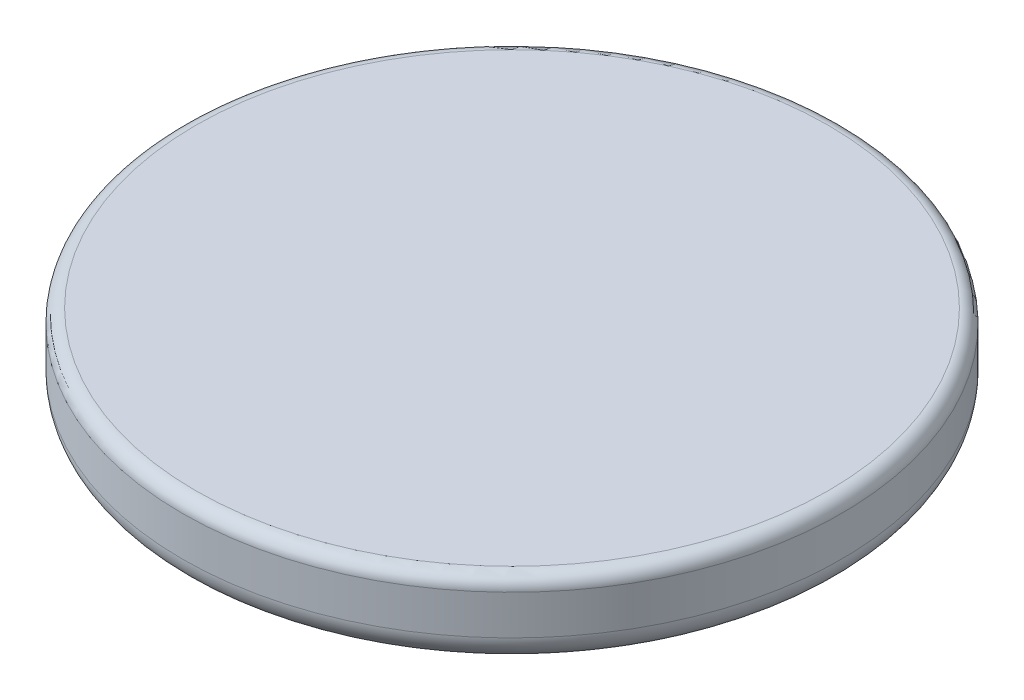
SolidWorks part; units mm, degrees
ref_plane "Front Plane" through (0, 0, 0) normal (0, 0, 1) x (1, 0, 0)
ref_plane "Top Plane" through (0, 0, 0) normal (0, 1, 0) x (1, 0, 0)
ref_plane "Right Plane" through (0, 0, 0) normal (1, 0, 0) x (0, 0, -1)
sketch "Sketch1" plane through (0, 0, 0) normal (0, 1, 0) x (1, 0, 0)
  circle A0 centre (0, 0) radius 31.75
  dimension "D1" = 63.5
extrude "Boss-Extrude1" add sketch "Sketch1" along normal blind 7.62
sketch "Sketch2" plane through (0, 0, 0) normal (0, -1, 0) x (1, 0, 0)
  circle A0 centre (0, 0) radius 3.683
  dimension "D1" = 7.366
extrude "Boss-Extrude2" add sketch "Sketch2" along normal blind 12.7
fillet "Fillet1" radius 1.27 1 edges at (0, 7.62, 31.75)
fillet "Fillet2" radius 2.54 1 edges at (0, 0, 31.75)
